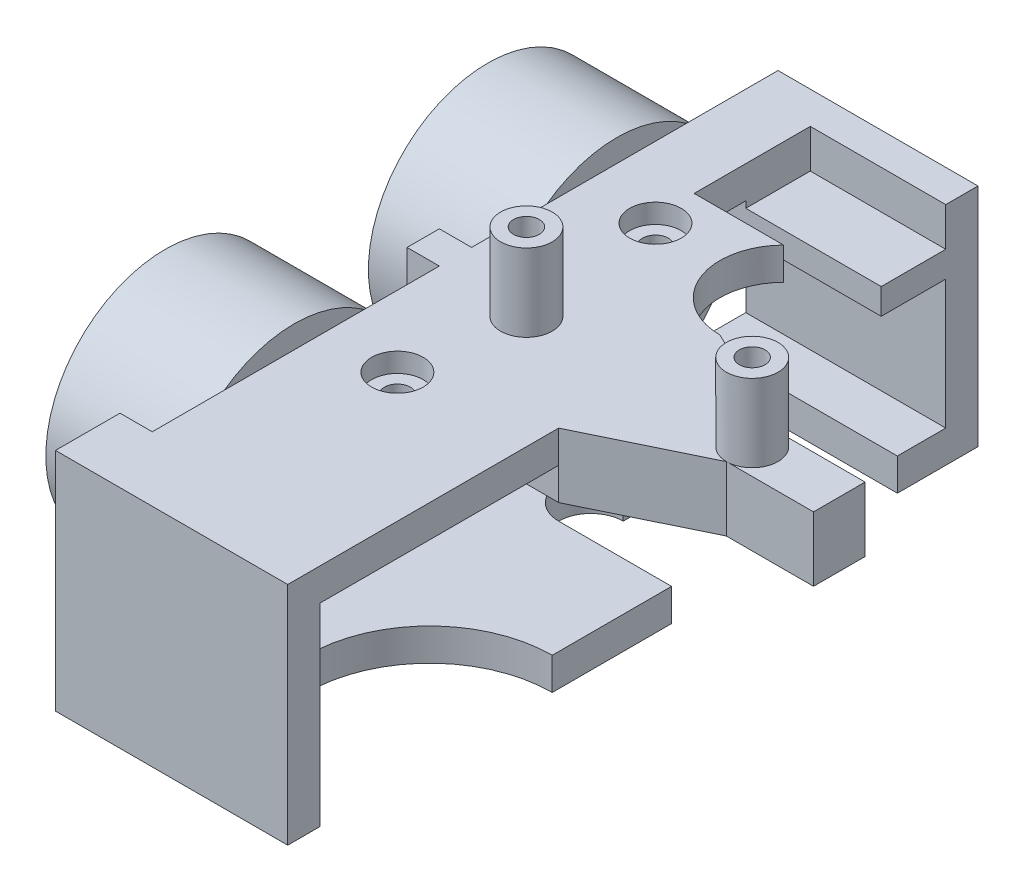
SolidWorks part; units mm, degrees
ref_plane "前视基准面" through (0, 0, 0) normal (0, 0, 1) x (1, 0, 0)
ref_plane "上视基准面" through (0, 0, 0) normal (0, 1, 0) x (1, 0, 0)
ref_plane "右视基准面" through (0, 0, 0) normal (1, 0, 0) x (0, 0, -1)
other "Configuration Table"
sketch "草图1" plane through (0, 0, 0) normal (0, 1, 0) x (1, 0, 0)
  line L0 (-1011.4129, 45) -> (48988.5871, 45) construction
  line L1 (-20, -20) -> (20, -20) construction
  line L2 (-20, -20) -> (-20, 20) construction
  line L3 (-20, 20) -> (20, 20) construction
  line L4 (20, -20) -> (20, 20) construction
  line L5 (-20, -20) -> (20, 20) construction
  line L6 (-20, 20) -> (20, -20) construction
  line L7 (0, -1000) -> (0, 49000) construction
  line L8 (-31, 45) -> (31, 45)
  line L9 (31, 45) -> (31, -45)
  line L10 (31, -45) -> (-31, -45)
  line L11 (-31, -45) -> (-31, 45)
  line L12 (-1000, 0) -> (49000, 0) construction
  circle A0 centre (-20, 20) radius 5
  circle A1 centre (20, 20) radius 5
  circle A2 centre (20, -20) radius 5
  circle A3 centre (-20, -20) radius 5
  circle A4 centre (0, 20) radius 10
  point P0 (0, 0)
  dimension "D3" = 10
  dimension "D4" = 10
  dimension "D5" = 10
  dimension "D6" = 10
  dimension "D9" = 20
  dimension "D1" = 40
  dimension "D2" = 40
  dimension "D7" = 25
  dimension "D8" = 62
extrude "凸台-拉伸1" add sketch "草图1" along normal blind 7
ref_plane "基准面1" through (0, -16, 0) normal (0, -1, 0) x (-1, 0, 0)
sketch "草图3" plane through (0, -16, 0) normal (0, -1, 0) x (-1, 0, 0)
  line L0 (0, -35) -> (0, 0) construction
  line L1 (-17.5, 7.5) -> (17.5, 7.5) construction
  line L2 (-17.5, 7.5) -> (-17.5, 32.5) construction
  line L3 (-17.5, 32.5) -> (17.5, 32.5) construction
  line L4 (17.5, 7.5) -> (17.5, 32.5) construction
  line L5 (-17.5, 7.5) -> (17.5, 32.5) construction
  line L6 (-17.5, 32.5) -> (17.5, 7.5) construction
  line L7 (-31, 45) -> (31, 45)
  line L8 (31, 45) -> (31, -45)
  line L9 (31, -45) -> (16.1555, -45)
  line L10 (-31, -45) -> (-31, 45)
  line L11 (-16.1555, -45) -> (-31, -45)
  circle A0 centre (0, 20) radius 10
  circle A1 centre (17.5, 32.5) radius 5
  circle A2 centre (17.5, 7.5) radius 5
  circle A3 centre (-17.5, 7.5) radius 5
  circle A4 centre (-17.5, 32.5) radius 5
  circle A5 centre (0, 20) radius 10 construction
  arc A6 (16.1555, -45) -> (-16.1555, -45) centre (0, -35) ccw
  dimension "D3" = 10
  dimension "D4" = 10
  dimension "D5" = 10
  dimension "D6" = 10
  dimension "D8" = 38
  dimension "D1" = 35
  dimension "D2" = 25
  dimension "D7" = 55
extrude "凸台-拉伸2" add sketch "草图3" along normal blind 7 separate body
sketch "草图4" plane through (31, 0, 0) normal (1, 0, 0) x (0, 0, -1)
  line L0 (-25, -3) -> (25, -3) construction
  line L1 (0, -1000) -> (0, 49000) construction
  line L2 (-45, 7) -> (-45, 0) construction
  line L3 (45, 7) -> (45, 0) construction
  line L4 (45, -23) -> (-45, -23) construction
  circle A0 centre (-25, -3) radius 20 construction
  circle A1 centre (25, -3) radius 20 construction
  circle A2 centre (-25, -3) radius 18.5
  circle A3 centre (25, -3) radius 18.5
  point P5 (0, -3)
  dimension "D1" = 40
  dimension "D2" = 37
  dimension "D3" = 37
extrude "凸台-拉伸3" add sketch "草图4" along normal blind 20
mirror "镜向1" about plane through (0, 0, 0) normal (1, 0, 0) of "凸台-拉伸3"
sketch "草图5" plane through (0, 7, 0) normal (0, 1, 0) x (1, 0, 0)
  line L0 (-21, 45) -> (21, 45)
  line L1 (31, 45) -> (-31, 45) construction
  line L2 (21, 45) -> (21, 27)
  line L3 (21, 27) -> (-21, 27)
  line L4 (-21, 27) -> (-21, 45)
  line L5 (-31, 9.4356) -> (-31, 40.5644) construction
  line L6 (31, 40.5644) -> (31, 9.4356) construction
  dimension "D1" = 10
  dimension "D2" = 10
  dimension "D3" = 18
extrude "切除-拉伸1" cut sketch "草图5" against normal blind 7
sketch "草图7" plane through (0, 7, 0) normal (0, 1, 0) x (1, 0, 0)
  line L0 (-7.1414, 27) -> (-21, 27)
  line L1 (-21, 45) -> (-21, 27) construction
  line L2 (-21, 27) -> (-21, 45)
  line L3 (-21, 45) -> (-31, 45)
  line L4 (-31, 45) -> (-31, -45)
  line L5 (-31, -45) -> (31, -45)
  line L6 (31, -45) -> (31, 45)
  line L7 (31, 45) -> (21, 45)
  line L8 (21, 45) -> (21, 27)
  line L9 (21, 27) -> (21, 45) construction
  line L10 (21, 27) -> (7.1414, 27)
  arc A2 (-7.1414, 27) -> (7.1414, 27) centre (0, 20) ccw
  circle A3 centre (-20, 20) radius 2
  circle A4 centre (20, 20) radius 2
  circle A5 centre (20, -20) radius 2
  circle A6 centre (-20, -20) radius 2
  dimension "D1" = 4
  dimension "D2" = 4
  dimension "D3" = 4
  dimension "D4" = 4
extrude "凸台-拉伸5" add sketch "草图7" along normal blind 5
sketch "草图6" plane through (0, 12, 0) normal (0, 1, 0) x (1, 0, 0)
  line L0 (0, 20) -> (0, 10) construction
  line L2 (-17.5, -2.5) -> (17.5, -2.5) construction
  line L3 (-17.5, -2.5) -> (-17.5, 22.5) construction
  line L4 (-17.5, 22.5) -> (17.5, 22.5) construction
  line L5 (17.5, -2.5) -> (17.5, 22.5) construction
  line L6 (-17.5, -2.5) -> (17.5, 22.5) construction
  line L7 (-17.5, 22.5) -> (17.5, -2.5) construction
  circle A1 centre (-17.5, 22.5) radius 4 construction
  circle A2 centre (-17.5, 22.5) radius 2 construction
  circle A3 centre (-17.5, -2.5) radius 2
  circle A4 centre (-17.5, -2.5) radius 4
  circle A5 centre (17.5, -2.5) radius 2
  circle A6 centre (17.5, -2.5) radius 4
  circle A7 centre (17.5, 22.5) radius 4 construction
  circle A8 centre (17.5, 22.5) radius 2 construction
  dimension "D4" = 8
  dimension "D5" = 4
  dimension "D6" = 8
  dimension "D7" = 4
  dimension "D1" = 10
  dimension "D2" = 35
  dimension "D3" = 25
extrude "凸台-拉伸7" add sketch "草图6" along normal blind 12
sketch "草图18" plane through (0, 12, 0) normal (0, 1, 0) x (1, 0, 0)
  circle A0 centre (-20, 20) radius 4
  circle A1 centre (20, 20) radius 4
  circle A2 centre (20, -20) radius 4
  circle A3 centre (-20, -20) radius 4
  dimension "D1" = 8
  dimension "D2" = 8
  dimension "D3" = 8
  dimension "D4" = 8
extrude "切除-拉伸8" cut sketch "草图18" against normal blind 3
sketch "草图9" plane through (0, 0, 0) normal (0, 1, 0) x (1, 0, 0)
  line L0 (0, -1000) -> (0, 49000) construction
  line L3 (58.169, 1.5) -> (58.169, 54.5405)
  line L4 (58.169, 54.5405) -> (0, 54.5405)
  line L6 (0, -53.3021) -> (58.169, -53.3021)
  line L7 (58.169, -53.3021) -> (58.169, -6.5)
  line L9 (-982.5, -2.5) -> (49017.5, -2.5) construction
  line L10 (58.169, 1.5) -> (58.169, -6.5) construction
  line L11 (0, 54.5405) -> (0, 10)
  line L12 (0, 10) -> (17.5, 1.5)
  line L13 (17.5, 1.5) -> (58.169, 1.5)
  line L14 (58.169, -6.5) -> (17.5, -6.5)
  line L15 (0, -53.3021) -> (0, -15)
  line L16 (0, -15) -> (17.5, -6.5)
  line L17 (17.5, 1.5) -> (17.5, -6.5) construction
  arc A1 (-7.1414, 27) -> (7.1414, 27) centre (0, 20) ccw construction
  circle A2 centre (17.5, -2.5) radius 4 construction
  point P23 (17.5, -2.5)
extrude "切除-拉伸3" cut sketch "草图9" against normal through all both and the other way through all
sketch "草图10" plane through (0, 0, 0) normal (0, 1, 0) x (1, 0, 0)
  line L0 (-21, 27) -> (-21, 15.101)
  line L1 (-21, 15.101) -> (-7.1414, 15.101)
  line L2 (-7.1414, 15.101) -> (-7.1414, 27)
  line L3 (-7.1414, 27) -> (-21, 27)
  line L4 (-20, -15) -> (-20, -45)
  line L5 (-20, -45) -> (0, -45)
  line L6 (0, -15) -> (0, -45) construction
  line L7 (0, -45) -> (0, -15)
  line L8 (0, -15) -> (-20, -15)
  line L9 (-7.1414, 27) -> (-21, 27) construction
  line L10 (-31, -45) -> (0, -45) construction
  circle A0 centre (-20, 20) radius 5 construction
  circle A2 centre (-20, -20) radius 5 construction
extrude "切除-拉伸4" cut sketch "草图10" along normal up to surface (7 mm away) up to face at (-20, 7, 25)
sketch "草图11" plane through (0, -16, 0) normal (0, 1, 0) x (1, 0, 0)
  line L0 (-17.5, 37.5) -> (0, 37.5)
  line L1 (0, 45) -> (0, 30) construction
  line L2 (0, 37.5) -> (0, 27.5)
  line L3 (0, 27.5) -> (-17.5, 27.5)
  line L4 (-17.5, 27.5) -> (-17.5, 37.5)
  line L5 (-17.5, 12.5) -> (32.6555, 12.5)
  line L6 (32.6555, 12.5) -> (32.6555, -18.1888)
  line L7 (32.6555, -18.1888) -> (0, -18.1888)
  line L8 (0, -18.1888) -> (0, 2.5)
  line L9 (0, 2.5) -> (-17.5, 2.5)
  line L10 (-17.5, 2.5) -> (-17.5, 12.5)
  circle A0 centre (-17.5, 32.5) radius 5 construction
  circle A1 centre (-17.5, 7.5) radius 5 construction
extrude "切除-拉伸5" cut sketch "草图11" against normal up to surface (7 mm away) up to face at (0.027, -23, -0.3122)
sketch "草图19" plane through (0, -23, 0) normal (0, -1, 0) x (1, 0, 0)
  line L0 (-17.5, -12.5) -> (-17.5, -27.5)
  line L1 (-17.5, -27.5) -> (-6.6144, -27.5)
  line L2 (-6.6144, -27.5) -> (-6.6144, -12.5)
  line L3 (-6.6144, -12.5) -> (-17.5, -12.5)
extrude "切除-拉伸9" cut sketch "草图19" against normal up to next
sketch "草图12" plane through (0, 0, 0) normal (0, -1, 0) x (1, 0, 0)
  line L0 (-31, 45) -> (-31, -45)
  line L1 (-31, -45) -> (61.9773, -45)
  line L2 (61.9773, -45) -> (61.9773, 45)
  line L3 (61.9773, 45) -> (-31, 45)
extrude "切除-拉伸6" cut sketch "草图12" against normal blind 2
sketch "草图13" plane through (0, -16, 0) normal (0, 1, 0) x (1, 0, 0)
  line L0 (-31, 45) -> (-31, -45)
  line L1 (-31, -45) -> (36.2674, -45)
  line L2 (36.2674, -45) -> (36.2674, 45)
  line L3 (36.2674, 45) -> (-31, 45)
extrude "切除-拉伸7" cut sketch "草图13" against normal blind 2
sketch "草图14" plane through (0, 0, -45) normal (0, 0, -1) x (-1, 0, 0)
  line L0 (31, 12) -> (31, -23)
  line L1 (31, -23) -> (0, -23)
  line L2 (0, -23) -> (0, 12)
  line L3 (0, 12) -> (31, 12)
extrude "凸台-拉伸8" add sketch "草图14" along normal blind 5
sketch "草图15" plane through (0, 0, 45) normal (0, 0, 1) x (1, 0, 0)
  line L4 (0, 12) -> (0, 7)
  line L5 (0, 7) -> (-20, 7)
  line L6 (-20, 7) -> (-20, 2)
  line L7 (-20, 2) -> (-31, 2)
  line L8 (-31, 2) -> (-31, 12)
  line L9 (-31, 12) -> (0, 12) construction
  line L10 (-31, 12) -> (-31, 2) construction
  line L11 (-31, 12) -> (0, 12)
  line L12 (-16.1555, -18) -> (-31, -18)
  line L13 (-31, -18) -> (-31, -23)
  line L14 (-31, -23) -> (-16.1555, -23)
  line L15 (-16.1555, -23) -> (-16.1555, -18)
extrude "凸台-拉伸9" add sketch "草图15" along normal blind 7
sketch "草图16" plane through (0, 0, 52) normal (0, 0, 1) x (1, 0, 0)
  line L0 (-31, 12) -> (0, 12)
  line L1 (0, 12) -> (0, -23)
  line L2 (0, -23) -> (-31, -23)
  line L3 (-31, -23) -> (-31, 12)
  point P8 (0, 0)
extrude "凸台-拉伸10" add sketch "草图16" along normal blind 5
sketch "草图20" plane through (0, 2, 0) normal (0, -1, 0) x (1, 0, 0)
  line L0 (-21, -45) -> (0, -45)
  line L1 (0, -45) -> (0, -35)
  line L2 (0, -35) -> (-21, -35)
  line L3 (-21, -45) -> (-21, -24.899) construction
  line L4 (-21, -35) -> (-21, -45)
  point P3 (-0.0875, -45)
  point P8 (-1.9138, -45)
  dimension "D1" = 10
extrude "凸台-拉伸11" add sketch "草图20" against normal blind 4
sketch "草图21" plane through (-31, 0, 0) normal (-1, 0, 0) x (0, 0, 1)
  line L0 (-2.5, 12) -> (2.5, 12)
  line L1 (-14.1718, 12) -> (14.1718, 12) construction
  line L2 (2.5, 12) -> (2.5, -23)
  line L3 (57, -23) -> (-50, -23) construction
  line L4 (2.5, -23) -> (-2.5, -23)
  line L5 (-2.5, -23) -> (-2.5, 12)
  line L6 (0, 12) -> (0, -23) construction
  line L7 (57, 12) -> (47, 12)
  line L8 (35.8282, 12) -> (57, 12) construction
  line L9 (47, 12) -> (47, -23)
  line L10 (47, -23) -> (57, -23)
  line L11 (57, -23) -> (57, 12)
  dimension "D1" = 5
  dimension "D2" = 10
extrude "凸台-拉伸12" add sketch "草图21" along normal blind 5
sketch "草图22" plane through (-51, 0, 0) normal (-1, 0, 0) x (0, 0, 1)
  circle A0 centre (-25, -3) radius 10
  circle A1 centre (25, -3) radius 10
  dimension "D1" = 20
  dimension "D2" = 20
extrude "切除-拉伸10" cut sketch "草图22" against normal through all
sketch "草图23" plane through (-20, 0, 0) normal (1, 0, 0) x (0, 0, -1)
  line L0 (-35, -3) -> (-35, 7)
  line L1 (-52, 7) -> (-15, 7) construction
  line L2 (-35, 7) -> (-15, 7)
  line L3 (-25, 7) -> (-15, 7) construction
  line L4 (-15, 7) -> (-15, -3)
  line L5 (-15, -3) -> (-35, -3)
  line L6 (15, -3) -> (35, -3)
  line L7 (35, -3) -> (35, 7)
  line L8 (35, 7) -> (15.101, 7)
  line L9 (15.101, 7) -> (15, -3)
  arc A0 (-33.6603, 2) -> (-16.3397, 2) centre (-25, -3) ccw construction
  arc A1 (16.3397, 2) -> (33.6603, 2) centre (25, -3) ccw construction
  point P11 (25, -3)
  point P13 (-25, -3)
extrude "切除-拉伸11" cut sketch "草图23" against normal up to surface (11 mm away) up to face at (-31, 13.75, 25)
